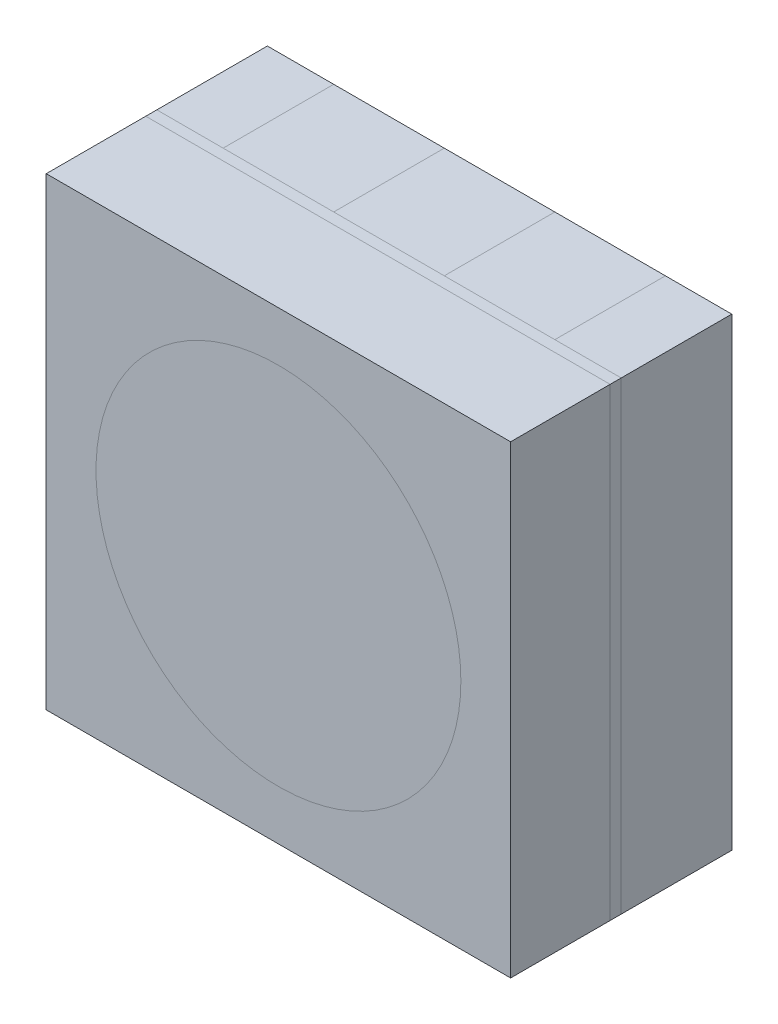
SolidWorks part; units mm, degrees
ref_plane "Front Plane" through (0, 0, 0) normal (0, 0, 1) x (1, 0, 0)
ref_plane "Top Plane" through (0, 0, 0) normal (0, 1, 0) x (1, 0, 0)
ref_plane "Right Plane" through (0, 0, 0) normal (1, 0, 0) x (0, 0, -1)
sketch "Sketch1" plane through (0, 0, 0) normal (0, 0, 1) x (1, 0, 0)
  line L1 (0, 0) -> (2.1, 0)
  line L2 (0, 0) -> (0, 2.1)
  line L3 (0, 2.1) -> (2.1, 2.1)
  line L4 (2.1, 0) -> (2.1, 2.1)
  dimension "D1" = 2.1
extrude "Boss-Extrude1" add sketch "Sketch1" along normal blind 0.45
sketch "Sketch2" plane through (0, 0, 0) normal (0, 0, -1) x (-1, 0, 0)
  line L4 (0, 0) -> (0, 2.1)
  line L5 (0, 2.1) -> (-2.1, 2.1)
  line L6 (-2.1, 2.1) -> (-2.1, 0)
  line L7 (-2.1, 0) -> (0, 0)
  line L8 (0, 0) -> (0, 2.1)
  line L9 (0, 2.1) -> (-2.1, 2.1)
  line L10 (-2.1, 2.1) -> (-2.1, 0)
  line L11 (-2.1, 0) -> (0, 0)
  dimension "D1" = 0
extrude "Boss-Extrude2" add sketch "Sketch2" along normal blind 0.05 separate body
sketch "Sketch3" plane through (0, 0, -0.05) normal (0, 0, -1) x (-1, 0, 0)
  line L0 (0, 2.1) -> (-2.1, 2.1) construction
  line L1 (-0.3, 2.1) -> (-0.8, 2.1)
  line L2 (-0.3, 2.1) -> (-0.3, 1.6)
  line L3 (-0.3, 1.6) -> (-0.8, 1.6)
  line L4 (-0.8, 2.1) -> (-0.8, 1.6)
  line L5 (-1.05, 2.1) -> (-1.05, 0) construction
  line L6 (-1.3, 2.1) -> (-1.8, 2.1)
  line L7 (-1.3, 2.1) -> (-1.3, 1.6)
  line L8 (-1.3, 1.6) -> (-1.8, 1.6)
  line L9 (-1.8, 2.1) -> (-1.8, 1.6)
  line L10 (-2.1, 0) -> (0, 0) construction
  line L12 (-1.8, 0) -> (-1.3, 0)
  line L13 (-1.8, 0) -> (-1.8, 0.5)
  line L14 (-1.8, 0.5) -> (-1.3, 0.5)
  line L15 (-1.3, 0) -> (-1.3, 0.5)
  line L16 (-0.8, 0) -> (-0.3, 0)
  line L17 (-0.8, 0) -> (-0.8, 0.5)
  line L18 (-0.8, 0.5) -> (-0.3, 0.5)
  line L19 (-0.3, 0) -> (-0.3, 0.5)
  point P22 (-0.3263, 1.6)
  dimension "D1" = 0.5
  dimension "D2" = 1.5
extrude "Boss-Extrude3" add sketch "Sketch3" along normal blind 0.5 separate body
sketch "Sketch4" plane through (0, 0, -0.05) normal (0, 0, -1) x (-1, 0, 0)
  line L0 (-1.8, 0.5) -> (-1.8, 0) construction
  line L1 (-1.8, 0) -> (-1.3, 0) construction
  line L2 (-1.3, 0) -> (-1.3, 0.5) construction
  line L3 (-1.3, 0.5) -> (-1.8, 0.5) construction
  line L4 (-2.1, 0) -> (0, 0)
  line L5 (0, 0) -> (0, 2.1)
  line L6 (0, 2.1) -> (-2.1, 2.1)
  line L7 (-2.1, 2.1) -> (-2.1, 0)
  line L8 (-2.1, 0) -> (0, 0)
  line L9 (0, 0) -> (0, 2.1)
  line L10 (0, 2.1) -> (-2.1, 2.1)
  line L11 (-2.1, 2.1) -> (-2.1, 0)
  line L12 (-0.8, 0.5) -> (-0.8, 0) construction
  line L13 (-0.8, 0) -> (-0.3, 0) construction
  line L14 (-0.3, 0) -> (-0.3, 0.5) construction
  line L15 (-0.3, 0.5) -> (-0.8, 0.5) construction
  line L16 (-0.3, 1.6) -> (-0.3, 2.1) construction
  line L17 (-0.3, 2.1) -> (-0.8, 2.1) construction
  line L18 (-0.8, 2.1) -> (-0.8, 1.6) construction
  line L19 (-0.8, 1.6) -> (-0.3, 1.6) construction
  line L20 (-1.3, 1.6) -> (-1.3, 2.1) construction
  line L21 (-1.3, 2.1) -> (-1.8, 2.1) construction
  line L22 (-1.8, 2.1) -> (-1.8, 1.6) construction
  line L23 (-1.8, 1.6) -> (-1.3, 1.6) construction
  line L24 (-1.8, 0.5) -> (-1.8, 0)
  line L25 (-1.8, 0) -> (-1.3, 0)
  line L26 (-1.3, 0) -> (-1.3, 0.5)
  line L27 (-1.3, 0.5) -> (-1.8, 0.5)
  line L28 (-0.8, 0.5) -> (-0.8, 0)
  line L29 (-0.8, 0) -> (-0.3, 0)
  line L30 (-0.3, 0) -> (-0.3, 0.5)
  line L31 (-0.3, 0.5) -> (-0.8, 0.5)
  line L32 (-0.3, 1.6) -> (-0.3, 2.1)
  line L33 (-0.3, 2.1) -> (-0.8, 2.1)
  line L34 (-0.8, 2.1) -> (-0.8, 1.6)
  line L35 (-0.8, 1.6) -> (-0.3, 1.6)
  line L36 (-1.3, 1.6) -> (-1.3, 2.1)
  line L37 (-1.3, 2.1) -> (-1.8, 2.1)
  line L38 (-1.8, 2.1) -> (-1.8, 1.6)
  line L39 (-1.8, 1.6) -> (-1.3, 1.6)
  line M5 (-2.1, 0) -> (0, 0)
  line M6 (0, 0) -> (0, 2.1)
  line M7 (0, 2.1) -> (-2.1, 2.1)
  line M8 (-2.1, 2.1) -> (-2.1, 0)
  dimension "D1" = 0
extrude "Boss-Extrude5" add sketch "Sketch4" along normal blind 0.5 separate body contours L39 L38 L24 L27 L26 L28 L31 L30 L32 L35 L34 L36 M7 M8 M5 M6
sketch "Sketch5" plane through (0, 0, 0.45) normal (0, 0, 1) x (1, 0, 0)
  line L0 (2.1, 2.1) -> (0, 0) construction
  circle A0 centre (1.05, 1.05) radius 0.825
  point P6 (0, 0)
  dimension "D1" = 1.65
extrude "Cut-Extrude1" cut sketch "Sketch5" against normal blind 0.45
sketch "Sketch6" plane through (0, 0, 0) normal (0, 0, 1) x (1, 0, 0)
  line L0 (1.05, 1.875) -> (1.05, 0.225) construction
  line L1 (0.95, 1.6) -> (1.15, 1.6)
  line L2 (0.95, 1.6) -> (0.95, 1.4)
  line L3 (0.95, 1.4) -> (1.15, 1.4)
  line L4 (1.15, 1.6) -> (1.15, 1.4)
  line L5 (0.95, 1.15) -> (1.15, 1.15)
  line L6 (0.95, 1.15) -> (0.95, 0.95)
  line L7 (0.95, 0.95) -> (1.15, 0.95)
  line L8 (1.15, 1.15) -> (1.15, 0.95)
  line L9 (0.95, 0.7) -> (1.15, 0.7)
  line L10 (0.95, 0.7) -> (0.95, 0.5)
  line L11 (0.95, 0.5) -> (1.15, 0.5)
  line L12 (1.15, 0.7) -> (1.15, 0.5)
  line L13 (1.875, 1.05) -> (0.225, 1.05) construction
  line L14 (0, 1.05) -> (2.1, 1.05) construction
  line L15 (0, 2.1) -> (0, 0) construction
  line L16 (2.1, 0) -> (2.1, 2.1) construction
  circle A0 centre (1.05, 1.05) radius 0.825 construction
  dimension "D1" = 0.2
  dimension "D2" = 0.25
  dimension "D3" = 0.25
extrude "Boss-Extrude6" add sketch "Sketch6" along normal blind 0.25 separate body
sketch "Sketch7" plane through (0, 0, 0.45) normal (0, 0, 1) x (1, 0, 0)
  circle A0 centre (1.05, 1.05) radius 0.825 construction
  circle A1 centre (1.05, 1.05) radius 0.825
extrude "Boss-Extrude7" add sketch "Sketch7" against normal blind 0.1 separate body
